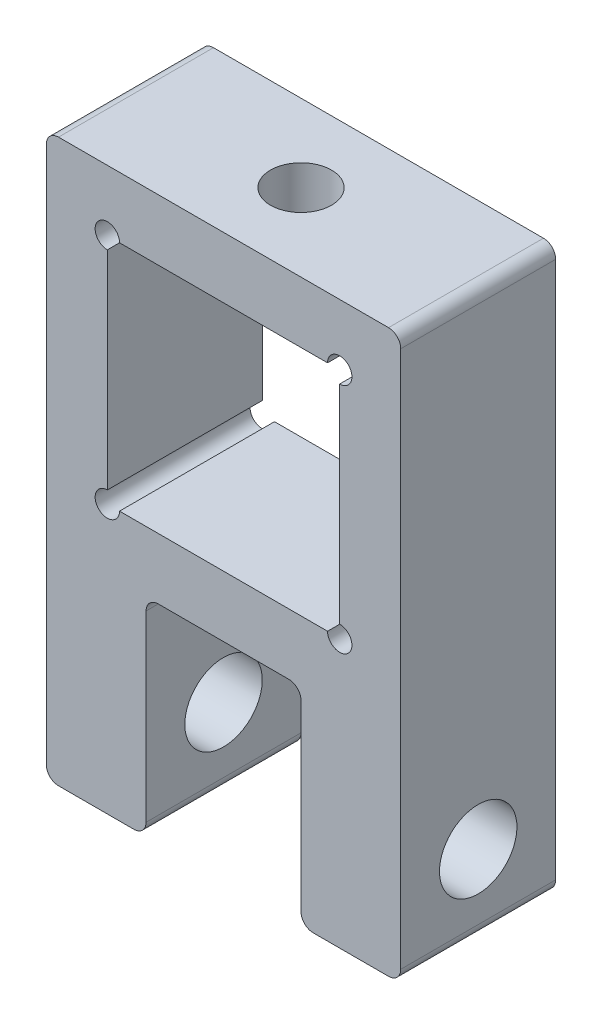
SolidWorks part; units mm, degrees
material "6061-T6 (SS)"
ref_plane "Plan de face" through (0, 0, 0) normal (0, 0, 1) x (1, 0, 0)
ref_plane "Plan de dessus" through (0, 0, 0) normal (0, 1, 0) x (1, 0, 0)
ref_plane "Plan de droite" through (0, 0, 0) normal (1, 0, 0) x (0, 0, -1)
sketch "Esquisse1" plane through (0, 0, 0) normal (0, 0, 1) x (1, 0, 0)
  line L0 (0, 0) -> (0, 79869.5619) construction
  line L1 (14.525, 46.05) -> (-14.525, 46.05)
  line L2 (-14.525, 46.05) -> (-14.525, 0)
  line L3 (-14.525, 0) -> (-6.35, 0)
  line L4 (-6.35, 0) -> (-6.35, 17)
  line L5 (-6.35, 17) -> (6.35, 17)
  line L6 (0, 17) -> (0, 22)
  line L7 (9.525, 22) -> (-9.525, 22)
  line L8 (-9.525, 22) -> (-9.525, 41.05)
  line L9 (-9.525, 41.05) -> (9.525, 41.05)
  line L10 (0, 41.05) -> (0, 46.05)
  line L11 (9.525, 22) -> (9.525, 41.05)
  line L12 (6.35, 0) -> (6.35, 17)
  line L13 (14.525, 0) -> (6.35, 0)
  line L14 (14.525, 46.05) -> (14.525, 0)
  circle A0 centre (-9.525, 41.05) radius 1
  circle A1 centre (-9.525, 22) radius 1
  circle A2 centre (9.525, 22) radius 1
  circle A3 centre (9.525, 41.05) radius 1
  dimension "D7" = 2
  dimension "D1" = 19.05
  dimension "D2" = 9.525
  dimension "D3" = 5
  dimension "D4" = 5
  dimension "D5" = 5
  dimension "D6" = 17
  dimension "D8" = 6.35
extrude "Boss.-Extru.1" add sketch "Esquisse1" along normal blind 12.7 contours A1 L8 A0 L9 L10 L1 L2 L3 L4 L5 L6 L7 | L9 A3 L11 A2 L7 L6 L5 L12 L13 L14 L1 L10
sketch "Esquisse2" plane through (-6.35, 0, 0) normal (1, 0, 0) x (0, 0, -1)
  line L0 (-6.35, 0) -> (-6.35, 50000) construction
  line L1 (-12.7, 0) -> (0, 0) construction
  circle A0 centre (-6.35, 6.35) radius 3.175
  point P4 (-6.35, 0)
  dimension "D1" = 6.35
  dimension "D2" = 6.35
extrude "Enlèv. mat.-Extru.1" cut sketch "Esquisse2" against normal through all both and the other way through all
fillet "Congé2" radius 1 8 edges at (14.525, 0, 6.35) (-14.525, 46.05, 6.35) (-14.525, 0, 6.35) (-6.35, 0, 6.35) (6.35, 0, 6.35) (6.35, 17, 6.35) (-6.35, 17, 6.35) (14.525, 46.05, 6.35)
sketch "Esquisse3" plane through (0, 46.05, 0) normal (0, 1, 0) x (1, 0, 0)
  line L0 (0, 0) -> (0, -12.7) construction
  line L1 (13.525, -12.7) -> (-13.525, -12.7) construction
  line L2 (-13.525, -6.35) -> (13.525, -6.35) construction
  line L3 (-13.525, 0) -> (-13.525, -12.7) construction
  line L4 (13.525, -12.7) -> (13.525, 0) construction
  circle A0 centre (0, -6.35) radius 2.5
  dimension "D1" = 5
extrude "Enlèv. mat.-Extru.2" cut sketch "Esquisse3" against normal up to next
